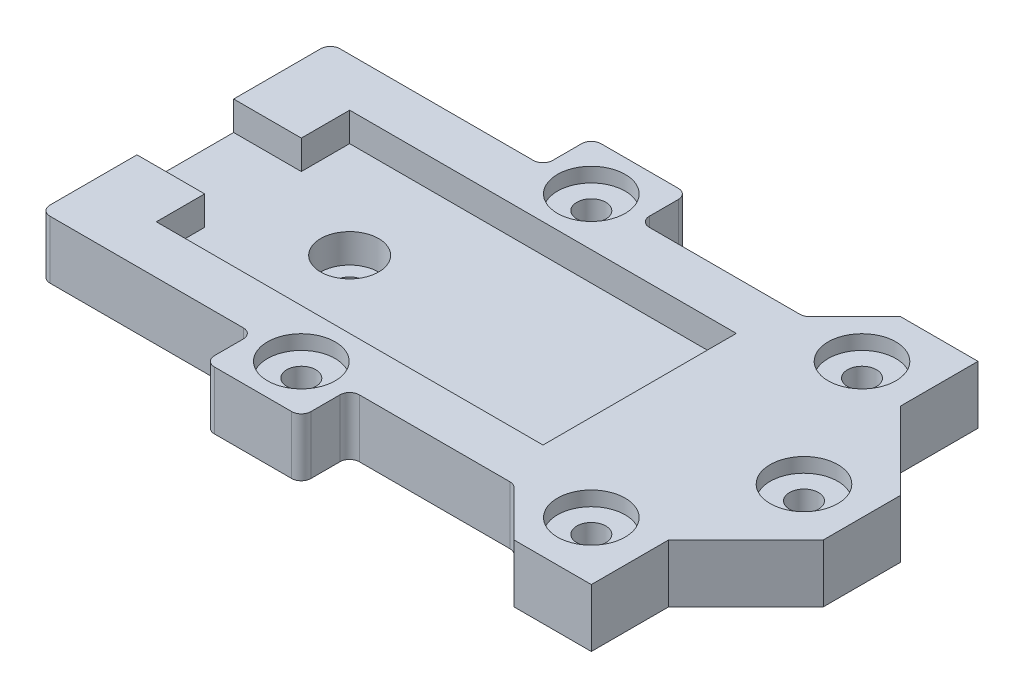
SolidWorks part; units mm, degrees
material "ABS"
ref_plane "前视基准面" through (0, 0, 0) normal (0, 0, 1) x (1, 0, 0)
ref_plane "上视基准面" through (0, 0, 0) normal (0, 1, 0) x (1, 0, 0)
ref_plane "右视基准面" through (0, 0, 0) normal (1, 0, 0) x (0, 0, -1)
sketch "草图1" plane through (0, 0, 0) normal (0, 1, 0) x (1, 0, 0)
  line L0 (0, 26.7143) -> (0, -26.4286) construction
  line L1 (-27, -15) -> (27, -15)
  line L2 (-27, -15) -> (-27, 15)
  line L3 (-27, 15) -> (27, 15)
  line L4 (27, -15) -> (27, 15)
  line L5 (-27, -15) -> (27, 15) construction
  line L6 (-27, 15) -> (27, -15) construction
  line L7 (-43.6667, 0) -> (48.8095, 0) construction
  line L8 (-5, 15) -> (-5, 20)
  line L9 (-5, 20) -> (5, 20)
  line L10 (5, 20) -> (5, 15)
  line L11 (5, -20) -> (5, -15)
  line L12 (-5, -20) -> (5, -20)
  line L13 (-5, -15) -> (-5, -20)
  line L14 (22, 15) -> (27, 20)
  line L15 (27, 20) -> (35, 20)
  line L16 (35, 20) -> (35, 12)
  line L17 (35, 12) -> (43, 4)
  line L18 (43, 4) -> (43, -4)
  line L19 (35, -12) -> (43, -4)
  line L20 (35, -20) -> (35, -12)
  line L21 (27, -20) -> (35, -20)
  line L22 (22, -15) -> (27, -20)
  circle A0 centre (0, 15) radius 1.5
  circle A1 centre (0, -15) radius 1.5
  circle A2 centre (29, 14) radius 1.5
  circle A3 centre (37, 0) radius 1.5
  circle A4 centre (29, -14) radius 1.5
  point P0 (0, 0)
  point P25 (43, 0)
  dimension "D10" = 3
  dimension "D11" = 3
  dimension "D13" = 3
  dimension "D1" = 30
  dimension "D2" = 54
  dimension "D3" = 5
  dimension "D4" = 10
  dimension "D5" = 5
  dimension "D6" = 8
  dimension "D7" = 5
  dimension "D8" = 8
  dimension "D9" = 4
  dimension "D12" = 6
  dimension "D14" = 6
  dimension "D15" = 6
extrude "凸台-拉伸1" add sketch "草图1" along normal blind 6 contours L1 A1 L4 L3 A0 L2 | A0 L3 L10 L9 L8 | L1 A1 L13 L12 L11 | L1 L22 L21 L20 L19 L18 L17 L16 L15 L14 L3 L4 A2 A3 A4
sketch "草图2" plane through (0, 6, 0) normal (0, 1, 0) x (1, 0, 0)
  line L0 (-20, 10) -> (-20, -10)
  line L1 (-20, -10) -> (20, -10)
  line L2 (20, -10) -> (20, 10)
  line L3 (20, 10) -> (-20, 10)
  line L4 (-27, -15) -> (-27, 15) construction
  line L5 (-27, 15) -> (-5, 15) construction
  line L6 (-32.9754, 0) -> (48.8868, 0) construction
  line L7 (-20, 5) -> (-27, 5)
  line L8 (-27, 5) -> (-27, -5)
  line L9 (-27, -5) -> (-20, -5)
  line M14 (-27, 15) -> (-27, -15)
  dimension "D1" = 7
  dimension "D2" = 5
  dimension "D3" = 20
  dimension "D4" = 40
  dimension "D5" = 10
extrude "切除-拉伸1" cut sketch "草图2" against normal blind 3 contours L6 L0 L7 M14 | L6 L8 L9 L0 | L0 L6 L2 L3 | L6 L0 L1 L2
sketch "草图3" plane through (0, 6, 0) normal (0, 1, 0) x (1, 0, 0)
  circle A0 centre (0, 15) radius 3.5
  circle A1 centre (0, -15) radius 3.5
  circle A2 centre (29, -14) radius 3.5
  circle A3 centre (37, 0) radius 3.5
  circle A4 centre (29, 14) radius 3.5
  dimension "D1" = 7
  dimension "D2" = 7
  dimension "D3" = 7
  dimension "D4" = 7
  dimension "D5" = 7
extrude "切除-拉伸2" cut sketch "草图3" against normal blind 1.5
sketch "草图5" plane through (0, 3, 0) normal (0, 1, 0) x (1, 0, 0)
  line L0 (-31.0228, 0) -> (46.5369, 0) construction
  line L1 (-20, 10) -> (-20, 5) construction
  circle A0 centre (-10, 0) radius 3
  dimension "D1" = 10
  dimension "D2" = 6
extrude "切除-拉伸3" cut sketch "草图5" against normal blind 3
sketch "草图6" plane through (0, 0, 0) normal (0, -1, 0) x (1, 0, 0)
  circle A0 centre (-10, 0) radius 6
  dimension "D1" = 12
extrude "凸台-拉伸2" add sketch "草图6" along normal blind 3.5
sketch "草图7" plane through (0, -3.5, 0) normal (0, -1, 0) x (1, 0, 0)
  circle A0 centre (-10, 0) radius 3
  dimension "D1" = 6
extrude "切除-拉伸4" cut sketch "草图7" against normal blind 1
sketch "草图8" plane through (0, -2.5, 0) normal (0, -1, 0) x (1, 0, 0)
  circle A0 centre (-10, 0) radius 1.5
  dimension "D1" = 3
extrude "切除-拉伸5" cut sketch "草图8" against normal through all
fillet "圆角1" radius 1 12 edges at (22, 3, 15) (5, 3, 15) (5, 3, 20) (-5, 3, 20) (-5, 3, 15) (-27, 3, 15) (-27, 3, -15) (-5, 3, -15) (-5, 3, -20) (5, 3, -20) (5, 3, -15) (22, 3, -15)
